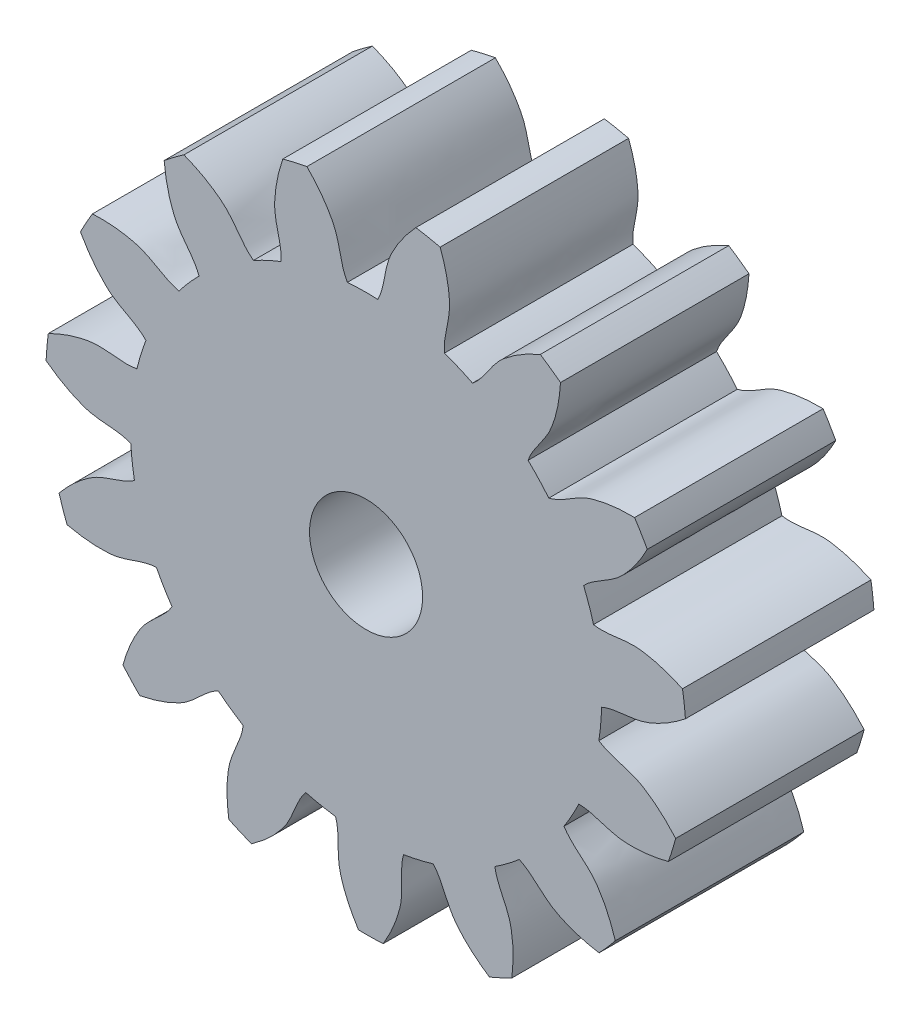
SolidWorks part; units mm, degrees
ref_plane "前视基准面" through (0, 0, 0) normal (0, 0, 1) x (1, 0, 0)
ref_plane "上视基准面" through (0, 0, 0) normal (0, 1, 0) x (1, 0, 0)
ref_plane "右视基准面" through (0, 0, 0) normal (1, 0, 0) x (0, 0, -1)
sketch "草图1" plane through (0, 0, 0) normal (0, 0, 1) x (1, 0, 0)
  circle A0 centre (0, 0) radius 6.25
  circle A1 centre (0, 0) radius 1.5
  dimension "D1" = 12.5
  dimension "D2" = 3
extrude "凸台-拉伸1" add sketch "草图1" along normal blind 5
sketch "草图2" plane through (0, 0, 0) normal (0, 0, 1) x (1, 0, 0)
  arc A0 (8.3938, 1.3394) -> (8.4721, 0.6879) centre (0, 0) cw
  arc A1 (6.033, 1.6328) -> (6.248, -0.1566) centre (0, 0) cw
  spline S0 degree 3 poles (8.4721, 0.6879) (8.2959, 0.5476) (8.0216, 0.3568) (7.6327, 0.1617) (7.0904, -0.0521) (6.5911, -0.0078) (6.248, -0.1566) knots 0 0 0 0 0.280058 0.412639 0.540236 1 1 1 1
  spline S1 degree 3 poles (8.3938, 1.3394) (8.1893, 1.4339) (7.8777, 1.5542) (7.4536, 1.6517) (6.8761, 1.7309) (6.4015, 1.5695) (6.033, 1.6328) knots 0 0 0 0 0.280058 0.412639 0.540236 1 1 1 1
extrude "凸台-拉伸2" add sketch "草图2" along normal blind 5
pattern_circular "阵列(圆周)1" count 15 over 360 about axis through (0, 0, 5) along (0, 0, -1) of "凸台-拉伸2"
